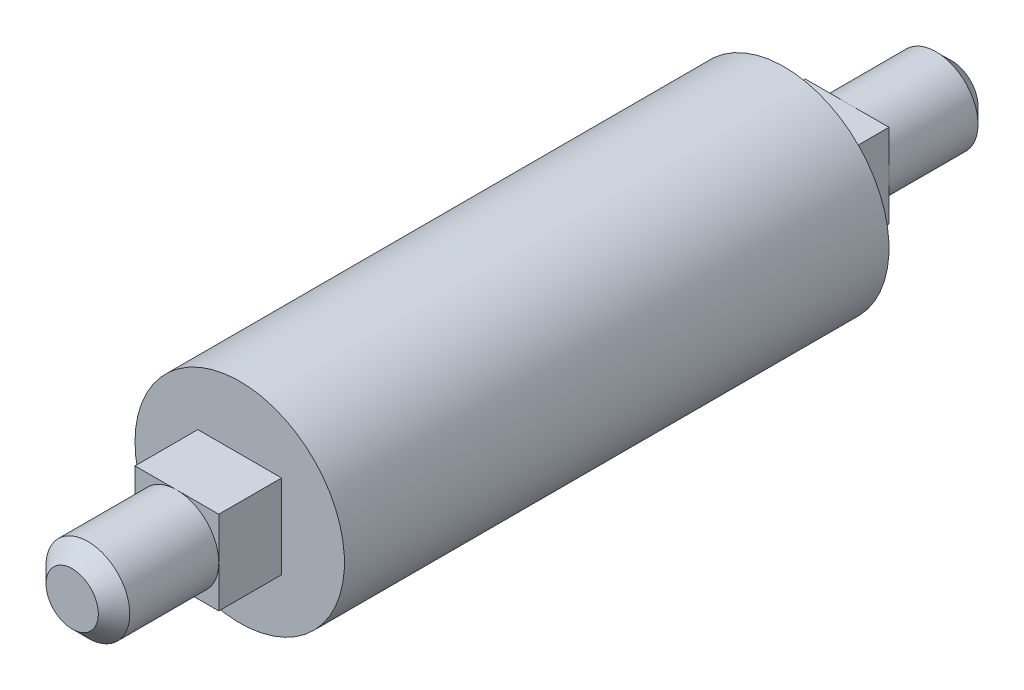
SolidWorks part; units mm, degrees
material "Messing"
ref_plane "Ebene vorne" through (0, 0, 0) normal (0, 0, 1) x (1, 0, 0)
ref_plane "Ebene oben" through (0, 0, 0) normal (0, 1, 0) x (1, 0, 0)
ref_plane "Ebene rechts" through (0, 0, 0) normal (1, 0, 0) x (0, 0, -1)
sketch "Skizze1" plane through (0, 0, 0) normal (0, 0, 1) x (1, 0, 0)
  circle A0 centre (0, 0) radius 10
  dimension "D1" = 20
extrude "Aufsatz-Linear austragen1" add sketch "Skizze1" along normal blind 26
sketch "Skizze2" plane through (0, 0, 26) normal (0, 0, 1) x (1, 0, 0)
  line L1 (4, -4) -> (-4, -4)
  line L2 (4, -4) -> (4, 4)
  line L3 (4, 4) -> (-4, 4)
  line L4 (-4, -4) -> (-4, 4)
  line L5 (4, -4) -> (-4, 4) construction
  line L6 (4, 4) -> (-4, -4) construction
  point P1 (0, 0)
  dimension "D1" = 8
  dimension "D2" = 8
extrude "Aufsatz-Linear austragen2" add sketch "Skizze2" along normal blind 6
sketch "Skizze3" plane through (0, 0, 32) normal (0, 0, 1) x (1, 0, 0)
  circle A0 centre (0, 0) radius 4
  dimension "D1" = 8
extrude "Aufsatz-Linear austragen3" add sketch "Skizze3" along normal blind 10
cosmetic thread "Gewindedarstellung1" parameters "D2"=6.619
chamfer "Fase1" distance 1.5 angle 45 1 edges at (4, 0, 42)
mirror "Spiegeln1" about plane through (0, 0, 0) normal (0, 0, 1) of bodies 103
